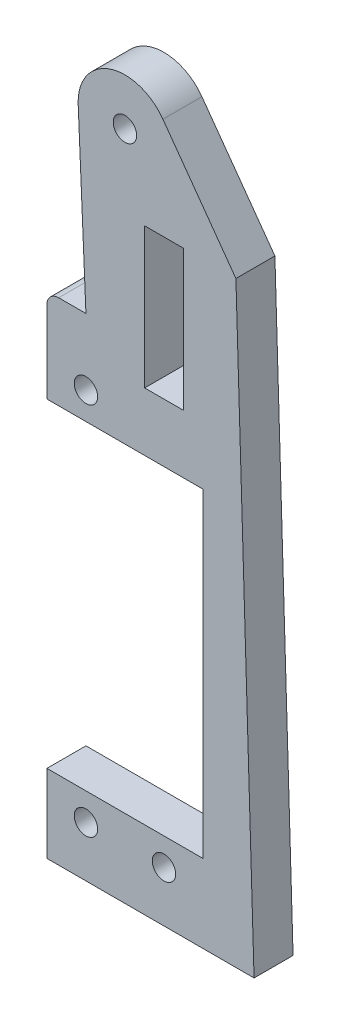
SolidWorks part; units mm, degrees
ref_plane "Plan de face" through (0, 0, 0) normal (0, 0, 1) x (1, 0, 0)
ref_plane "Plan de dessus" through (0, 0, 0) normal (0, 1, 0) x (1, 0, 0)
ref_plane "Plan de droite" through (0, 0, 0) normal (1, 0, 0) x (0, 0, -1)
sketch "Esquisse1" plane through (0, 0, 0) normal (0, 0, 1) x (1, 0, 0)
  line L0 (0, 10) -> (0, 0)
  line L1 (0, 0) -> (26.5541, 0)
  line L2 (10, 10) -> (10, 51) construction
  line L3 (0, 63) -> (5, 63)
  line L4 (12.5289, 76.5) -> (12.5289, 58.5)
  line L5 (11, 51) -> (0, 51)
  line L6 (12.5289, 76.5) -> (17.5289, 76.5)
  line L7 (20, 10) -> (11, 10)
  line L8 (0, 30.5) -> (0, 10)
  line L9 (0, 30.5) -> (20, 30.5) construction
  line L10 (20, 10) -> (20, 51)
  line L11 (20, 51) -> (11, 51)
  line L12 (14.8704, 89.5041) -> (24.2264, 76.5)
  line L13 (24.2264, 76.5) -> (26.5541, 0)
  line L14 (12.5289, 58.5) -> (17.5289, 58.5)
  line L15 (17.5289, 58.5) -> (17.5289, 76.5)
  line L16 (4.0057, 85.7379) -> (5, 63)
  line L18 (11, 10) -> (0, 10)
  line L25 (0, 63) -> (0, 51)
  line L26 (17.5289, 76.5) -> (24.2264, 76.5) construction
  circle A0 centre (5, 54.5) radius 1.5
  circle A1 centre (15, 54.5) radius 1.5 construction
  circle A2 centre (15, 6.5) radius 1.5
  circle A3 centre (5, 6.5) radius 1.5
  circle A4 centre (10, 86) radius 1.5
  arc A6 (4.0057, 85.7379) -> (14.8704, 89.5041) centre (10, 86) cw
  circle A7 centre (10, 86) radius 1.5 construction
  dimension "D6" = 20
  dimension "D8" = 5
  dimension "D11" = 3
  dimension "D16" = 10
  dimension "D5" = 3
  dimension "D12" = 91.743
  dimension "D13" = 6
  dimension "D1" = 41
  dimension "D2" = 12
  dimension "D3" = 3.5
  dimension "D4" = 5
  dimension "D7" = 5
  dimension "D9" = 5
  dimension "D10" = 18
extrude "Boss.-Extru.1" add sketch "Esquisse1" along normal blind 5
fillet "Congé3" radius 1.5 1 edges at (0, 63, 2.5)
